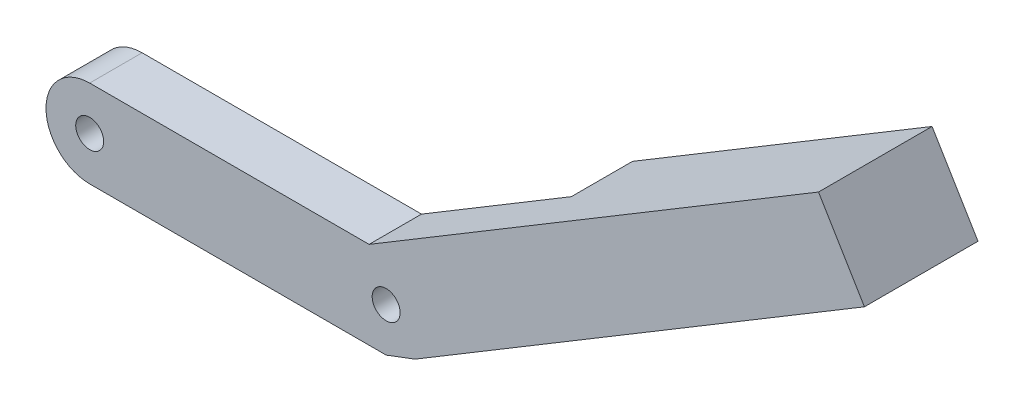
SolidWorks part; units mm, degrees
material "PLA"
ref_plane "Front Plane" through (0, 0, 0) normal (0, 0, 1) x (1, 0, 0)
ref_plane "Top Plane" through (0, 0, 0) normal (0, 1, 0) x (1, 0, 0)
ref_plane "Right Plane" through (0, 0, 0) normal (1, 0, 0) x (0, 0, -1)
sketch "Sketch1" plane through (0, 0, 0) normal (0, 0, 1) x (1, 0, 0)
  line L0 (0, 0) -> (33.93, 0) construction
  line L1 (0, 5) -> (33.93, 5)
  line L2 (0, -5) -> (33.93, -5)
  line L3 (31.98, 5) -> (37.2374, -3.7498) construction
  line L4 (31.98, 5) -> (83.41, 35.9023) construction
  line L5 (37.2374, -3.7498) -> (88.6675, 27.1525) construction
  line L6 (88.6675, 27.1525) -> (83.41, 35.9023)
  line L7 (31.98, 5) -> (83.41, 35.9023)
  line L12 (88.6675, 27.1525) -> (37.2374, -3.7498)
  line L24 (37.2374, -3.7498) -> (33.93, -5)
  arc A0 (0, 5) -> (0, -5) centre (0, 0) ccw
  arc A1 (33.93, -5) -> (33.93, 5) centre (33.93, 0) ccw
  circle A2 centre (0, 0) radius 1.6
  circle A3 centre (33.93, 0) radius 1.6
  point P3 (16.965, 0)
  dimension "D2" = 10
  dimension "D11" = 3.2
  dimension "D1" = 33.93
  dimension "D3" = 149
  dimension "D4" = 1.95
  dimension "D5" = 60
extrude "Boss-Extrude1" add sketch "Sketch1" along normal blind 6
fillet "Fillet1" [suppressed] radius 1
sketch "Croquis3" plane through (0, 0, 6) normal (0, 0, 1) x (1, 0, 0)
  line L0 (83.41, 35.9023) -> (88.6675, 27.1525)
  line L1 (88.6675, 27.1525) -> (54.3808, 6.551)
  line L2 (88.6675, 27.1525) -> (37.2374, -3.7498) construction
  line L3 (54.3808, 6.551) -> (49.1233, 15.3008)
  line L4 (31.98, 5) -> (83.41, 35.9023) construction
  line L5 (49.1233, 15.3008) -> (83.41, 35.9023)
  dimension "D1" = 40
extrude "Saliente-Extruir1" add sketch "Croquis3" against normal blind 7 from surface at -6 starting at face at (35.53, 0, 0)
